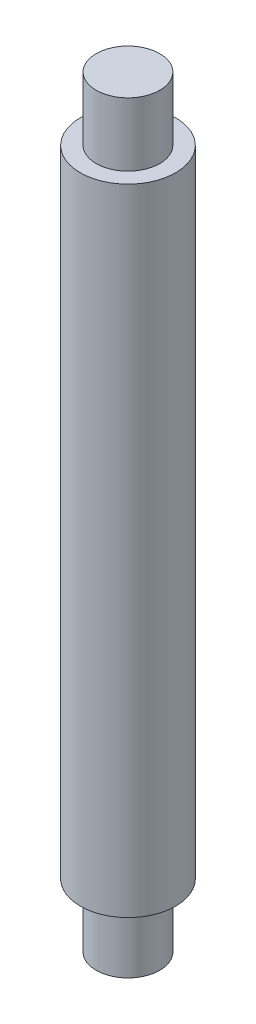
SolidWorks part; units mm, degrees
ref_plane "Plan de face" through (0, 0, 0) normal (0, 0, 1) x (1, 0, 0)
ref_plane "Plan de dessus" through (0, 0, 0) normal (0, 1, 0) x (1, 0, 0)
ref_plane "Plan de droite" through (0, 0, 0) normal (1, 0, 0) x (0, 0, -1)
sketch "Esquisse1" plane through (0, 0, 0) normal (0, 1, 0) x (1, 0, 0)
  circle A0 centre (0, 0) radius 3
  dimension "D1" = 6
extrude "Boss.-Extru.1" add sketch "Esquisse1" along normal blind 40
sketch "Esquisse2" plane through (0, 40, 0) normal (0, 1, 0) x (1, 0, 0)
  circle A0 centre (0, 0) radius 2
  dimension "D1" = 4
extrude "Boss.-Extru.2" add sketch "Esquisse2" along normal blind 4
sketch "Esquisse3" plane through (0, 0, 0) normal (0, -1, 0) x (1, 0, 0)
  circle A0 centre (0, 0) radius 2
  dimension "D1" = 4
extrude "Boss.-Extru.3" add sketch "Esquisse3" along normal blind 4
